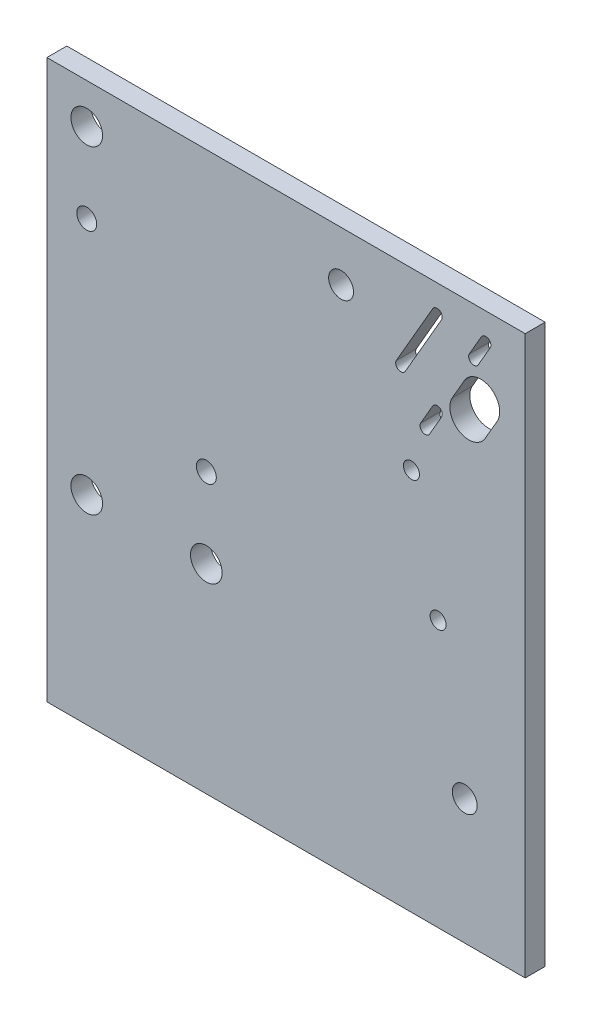
SolidWorks part; units mm, degrees
ref_plane "Front Plane" through (0, 0, 0) normal (1, 0, 0) x (0, 1, 0)
ref_plane "Top Plane" through (0, 0, 0) normal (0, 0, 1) x (0, 1, 0)
ref_plane "Right Plane" through (0, 0, 0) normal (0, 1, 0) x (-1, 0, 0)
sketch "Sketch2" plane through (0, 0, 0) normal (0, 0, 1) x (0, 1, 0)
  line L1 (0, 0) -> (177.8, 0)
  line L2 (0, 0) -> (0, 152.4)
  line L3 (0, 152.4) -> (177.8, 152.4)
  line L4 (177.8, 0) -> (177.8, 152.4)
  line L5 (63.5, 139.7) -> (165.1, 139.7) construction
  line L6 (63.5, 139.7) -> (63.5, 101.6) construction
  line L7 (63.5, 101.6) -> (165.1, 101.6) construction
  line L8 (165.1, 139.7) -> (165.1, 101.6) construction
  line L9 (63.5, 101.6) -> (124.236, 101.6) construction
  line L10 (63.5, 101.6) -> (63.5, 113.1176) construction
  line L11 (63.5, 113.1176) -> (124.236, 113.1176) construction
  line L12 (124.236, 101.6) -> (124.236, 113.1176) construction
  line L13 (63.5, 101.6) -> (139.7, 101.6) construction
  line L14 (63.5, 101.6) -> (63.5, 109.0554) construction
  line L15 (63.5, 109.0554) -> (139.7, 109.0554) construction
  line L16 (139.7, 101.6) -> (139.7, 109.0554) construction
  dimension "D2" = 12.7
  dimension "D3" = 12.7
  dimension "D4" = 38.1
  dimension "D5" = 177.8
  dimension "D6" = 152.4
  dimension "D7" = 11.5176
  dimension "D8" = 60.736
  dimension "D9" = 7.4554
  dimension "D10" = 76.2
  dimension "D11" = 101.6
extrude "Boss-Extrude1" add sketch "Sketch2" along normal blind 6.35
sketch "field_origin" plane through (0, 0, 0) normal (0, 0, -1) x (1, 0, 0)
  point P5 (-50.8, -222.25)
hole_wizard "3/8 Clearance Hole1" positions "Sketch3" profile "Sketch4" hole size "3/8" standard "ANSI Inch" end condition through all
sketch "Sketch3" plane through (0, 0, 6.35) normal (0, 0, 1) x (1, 0, 0)
  point P0 (-101.6, 63.5)
  point P3 (-139.7, 63.5)
  point P6 (-139.7, 165.1)
sketch "Sketch4" plane through (-101.6, 63.5, 6.35) normal (1, 0, 0) x (0, -1, 0)
  line L0 (0, 0) -> (0, 6.35)
  line L1 (0, 6.35) -> (5.0419, 6.35)
  line L2 (5.0419, 6.35) -> (5.0419, 0)
  line L5 (5.0419, 0) -> (0, 0)
  line L11 (0, -6.35) -> (0, 107.95) construction
  dimension "Thru Hole Dia." = 10.0838
  dimension "Thru Hole Depth" = 6.35
hole_wizard "Tap Drill for 1/4-20 Tap1" positions "Sketch7" profile "Sketch6" hole size "1/4-20" standard "ANSI Inch" end condition through all
sketch "Sketch7" plane through (0, 0, 6.35) normal (0, 0, 1) x (1, 0, 0)
  point P0 (-27.7546, 84.8487)
  point P3 (-36.2407, 122.0241)
  dimension "D1" = 100.2259
  dimension "D2" = 14.5593
  dimension "D3" = 137.4013
  dimension "D4" = 23.0454
sketch "Sketch6" plane through (-27.7546, 84.8487, 6.35) normal (1, 0, 0) x (0, -1, 0)
  line L0 (0, 0) -> (0, 6.35)
  line L1 (0, 6.35) -> (2.5527, 6.35)
  line L2 (2.5527, 6.35) -> (2.5527, 0)
  line L5 (2.5527, 0) -> (0, 0)
  line L11 (0, -6.35) -> (0, 107.95) construction
  dimension "Thru Hole Dia." = 5.1054
  dimension "Thru Hole Depth" = 6.35
sketch "Sketch8" plane through (0, 0, 6.35) normal (0, 0, 1) x (1, 0, 0)
  line L0 (-27.7546, 84.8487) -> (-152.4, -28.4904) construction
  line L1 (-36.2407, 122.0241) -> (-80.3848, 177.8) construction
  line L2 (0, 0) -> (0, 177.8) construction
  line L3 (-152.4, 177.8) -> (-152.4, 0) construction
  line L6 (0, 177.8) -> (-152.4, 177.8) construction
  line L7 (-87.3717, 30.6393) -> (-75.4292, 21.4295) construction
  line L8 (-30.8845, 115.2566) -> (-19.0589, 124.616) construction
  dimension "D1" = 38.36
  dimension "D2" = 47.72
  dimension "D3" = 15.0812
  dimension "D4" = 15.0812
sketch "Sketch13" plane through (0, 0, 0) normal (0, 0, -1) x (1, 0, 0)
  line L0 (-36.2407, -122.0241) -> (-145.707, -177.8) construction
  line L1 (0, -177.8) -> (-152.4, -177.8) construction
  line L2 (0, 0) -> (0, -177.8) construction
  line L3 (-70.1881, -139.3212) -> (-58.6567, -161.9527) construction
  line L4 (-27.7546, -84.8487) -> (-63.7707, 0) construction
  line L5 (-152.4, 0) -> (0, 0) construction
  line L6 (-42.6414, -49.7775) -> (-19.2606, -39.8529) construction
  point P8 (-58.6567, -161.9527)
  point P15 (-19.2606, -39.8529)
  point P18 (-58.6567, -161.9527)
  dimension "D1" = 63
  dimension "D2" = 23
  dimension "D3" = 25.4
  dimension "D4" = 38.1
  dimension "D5" = 25.4
  dimension "D6" = 38.1
hole_wizard "Tap Drill for 3/8-16 Tap3" positions "Sketch13" profile "Sketch16" hole size "3/8-16" standard "ANSI Inch" end condition through all
sketch "Sketch16" plane through (-58.6567, 161.9527, 0) normal (1, 0, 0) x (0, 1, 0)
  line L0 (0, 0) -> (0, 6.35)
  line L1 (0, 6.35) -> (3.9687, 6.35)
  line L2 (3.9687, 6.35) -> (3.9687, 0)
  line L5 (3.9687, 0) -> (0, 0)
  line L11 (0, -6.35) -> (0, 107.95) construction
  dimension "Thru Hole Dia." = 7.9375
  dimension "Thru Hole Depth" = 6.35
sketch "Sketch17" plane through (0, 0, 0) normal (0, 0, -1) x (1, 0, 0)
  line L0 (-139.7, -165.1) -> (-139.7, -139.7) construction
  line L1 (-139.7, -63.5) -> (-139.7, -165.1) construction
  line L3 (-139.7, -139.7) -> (-101.6, -139.7) construction
  line L4 (-139.7, -139.7) -> (-139.7, -88.9) construction
  line L5 (-139.7, -88.9) -> (-101.6, -88.9) construction
  line L6 (-101.6, -139.7) -> (-101.6, -88.9) construction
  point P1 (-139.7, -139.7)
  point P5 (-101.6, -88.9)
  dimension "D1" = 50.8
  dimension "D2" = 25.4
  dimension "D3" = 38.1
hole_wizard "1/4 (0.25) Diameter Hole1" positions "Sketch17" profile "Sketch18" hole size "1/4" standard "ANSI Inch" end condition through all
sketch "Sketch18" plane through (-101.6, 88.9, 0) normal (1, 0, 0) x (0, 1, 0)
  line L0 (0, 0) -> (0, 6.35)
  line L1 (0, 6.35) -> (3.175, 6.35)
  line L2 (3.175, 6.35) -> (3.175, 0)
  line L5 (3.175, 0) -> (0, 0)
  line L11 (0, -6.35) -> (0, 107.95) construction
  dimension "Thru Hole Dia." = 6.35
  dimension "Thru Hole Depth" = 6.35
sketch "Sketch19" plane through (0, 0, 0) normal (0, 0, -1) x (1, 0, 0)
  line L0 (-22.225, -152.4) -> (-10.6045, -145.6909) construction
  line L1 (-14.478, -165.8182) -> (-6.731, -152.4)
  line L2 (-6.731, -152.4) -> (-14.478, -138.9818)
  line L3 (-14.478, -138.9818) -> (-29.972, -138.9818)
  line L4 (-29.972, -138.9818) -> (-37.719, -152.4)
  line L5 (-37.719, -152.4) -> (-29.972, -165.8182)
  line L6 (-29.972, -165.8182) -> (-14.478, -165.8182)
  line L7 (0, -177.8) -> (-152.4, -177.8) construction
  line L8 (0, 0) -> (0, -177.8) construction
  circle A0 centre (-22.225, -152.4) radius 15.494 construction
  circle A1 centre (-16.0658, -148.844) radius 6.0325
  circle A2 centre (-22.225, -152.4) radius 18.415
  dimension "D3" = 12.065
  dimension "D4" = 36.83
  dimension "D1" = 7.112
  dimension "D2" = 30.988
  dimension "D5" = 25.4
  dimension "D6" = 22.225
  dimension "D7" = 0
sketch "Sketch20" plane through (0, 0, 0) normal (0, 0, -1) x (1, 0, 0)
  line L0 (-14.1608, -152.1436) -> (-17.9708, -145.5444) construction
  line L1 (-19.3851, -155.1598) -> (-23.1951, -148.5607)
  line L2 (-8.9365, -149.1273) -> (-12.7465, -142.5282)
  line L4 (-6.731, -152.4) -> (-14.478, -138.9818) construction
  arc A0 (-19.3851, -155.1598) -> (-8.9365, -149.1273) centre (-14.1608, -152.1436) ccw
  arc A1 (-12.7465, -142.5282) -> (-23.1951, -148.5607) centre (-17.9708, -145.5444) ccw
  circle A2 centre (-16.0658, -148.844) radius 6.0325 construction
  point P427 (-16.0658, -148.844)
  dimension "D1" = 7.62
sketch "Sketch22" plane through (0, 0, 0) normal (0, 0, -1) x (1, 0, 0)
  line L0 (-28.067, -142.2814) -> (-31.877, -135.6822) construction
  line L1 (-29.4803, -143.0973) -> (-33.2903, -136.4982)
  line L2 (-26.6537, -141.4654) -> (-30.4637, -134.8663)
  line L3 (-37.719, -152.4) -> (-29.972, -165.8182) construction
  line L4 (-28.067, -169.1178) -> (-39.624, -149.1004) construction
  line L5 (-29.4803, -169.9337) -> (-41.0373, -149.9164)
  line L6 (-26.6537, -168.3018) -> (-38.2107, -148.2845)
  line L7 (-12.573, -169.1178) -> (-16.383, -162.5186) construction
  line L8 (-13.9863, -169.9337) -> (-17.7963, -163.3346)
  line L9 (-11.1597, -168.3018) -> (-14.9697, -161.7027)
  arc A0 (-29.4803, -143.0973) -> (-26.6537, -141.4654) centre (-28.067, -142.2814) ccw
  arc A1 (-30.4637, -134.8663) -> (-33.2903, -136.4982) centre (-31.877, -135.6822) ccw
  arc A2 (-29.4803, -169.9337) -> (-26.6537, -168.3018) centre (-28.067, -169.1178) ccw
  arc A3 (-38.2107, -148.2845) -> (-41.0373, -149.9164) centre (-39.624, -149.1004) ccw
  arc A4 (-13.9863, -169.9337) -> (-11.1597, -168.3018) centre (-12.573, -169.1178) ccw
  arc A5 (-14.9697, -161.7027) -> (-17.7963, -163.3346) centre (-16.383, -162.5186) ccw
  point P0 (-33.8455, -159.1091)
  point P1 (-29.972, -138.9818)
  point P5 (-14.478, -165.8182)
  point P8 (-33.8455, -159.1091)
  point P12 (-29.972, -138.9818)
  point P25 (-14.478, -165.8182)
  dimension "D1" = 1.632
  dimension "D2" = 1.632
  dimension "D3" = 1.632
  dimension "D4" = 23.114
  dimension "D5" = 7.62
extrude "Cut-Extrude2" cut sketch "Sketch22" against normal through all
extrude "Cut-Extrude3" cut sketch "Sketch20" against normal through all
